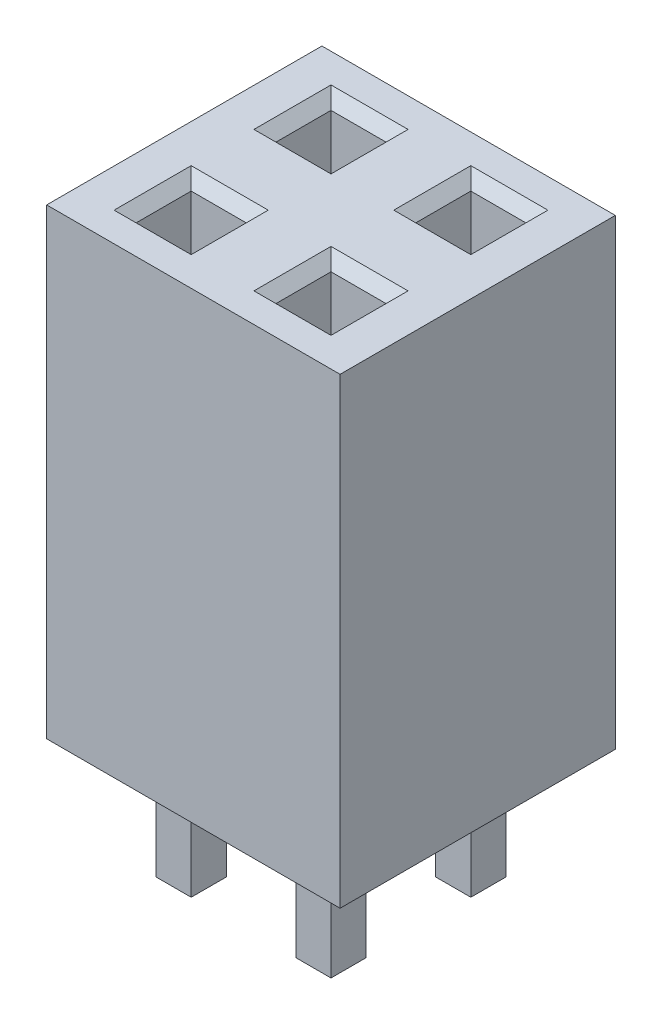
SolidWorks part; units mm, degrees
material "C (Графит)"
ref_plane "Спереди" through (0, 0, 0) normal (0, 0, 1) x (1, 0, 0)
ref_plane "Сверху" through (0, 0, 0) normal (0, 1, 0) x (1, 0, 0)
ref_plane "Справа" through (0, 0, 0) normal (1, 0, 0) x (0, 0, -1)
sketch "Эскиз1" plane through (0, 0, 0) normal (0, 1, 0) x (1, 0, 0)
  line L1 (-1.395, -2.5) -> (1.395, -2.5)
  line L2 (-1.395, -2.5) -> (-1.395, 2.5)
  line L3 (-1.395, 2.5) -> (1.395, 2.5)
  line L4 (1.395, -2.5) -> (1.395, 2.5)
  line L5 (-1.395, -2.5) -> (1.395, 2.5) construction
  line L6 (-1.395, 2.5) -> (1.395, -2.5) construction
  point P0 (0, 0)
  dimension "D1" = 5
  dimension "D2" = 2.79
extrude "Бобышка-Вытянуть1" add sketch "Эскиз1" along normal blind 8.4
sketch "Эскиз2" plane through (0, 8.4, 0) normal (0, 1, 0) x (1, 0, 0)
  line L0 (-1.395, 2.5) -> (-1.395, -2.5) construction
  line L1 (-0.5, 1.77) -> (0.5, 1.77)
  line L2 (-0.5, 1.77) -> (-0.5, 0.77)
  line L3 (-0.5, 0.77) -> (0.5, 0.77)
  line L4 (0.5, 1.77) -> (0.5, 0.77)
  line L5 (-0.5, 1.77) -> (0.5, 0.77) construction
  line L6 (-0.5, 0.77) -> (0.5, 1.77) construction
  line L7 (-1.395, 0) -> (-29.5201, 0) construction
  line L8 (0.5, -1.77) -> (0.5, -0.77)
  line L9 (-0.5, -0.77) -> (0.5, -0.77)
  line L10 (-0.5, -1.77) -> (-0.5, -0.77)
  line L11 (-0.5, -1.77) -> (0.5, -1.77)
  point P0 (0, 1.27)
  dimension "D1" = 1
  dimension "D2" = 1
  dimension "D3" = 1.395
  dimension "D4" = 1.27
extrude "Вырез-Вытянуть1" cut sketch "Эскиз2" against normal blind 8
chamfer "Фаска1" distance 0.2 angle 45 8 edges at (0.5, 8.4, -1.27) (0, 8.4, -0.77) (-0.5, 8.4, -1.27) (0, 8.4, -1.77) (0, 8.4, 1.77) (-0.5, 8.4, 1.27) (0, 8.4, 0.77) (0.5, 8.4, 1.27)
sketch "Эскиз3" plane through (0, 0, 0) normal (0, -1, 0) x (-1, 0, 0)
  line L0 (1.395, 2.5) -> (1.395, -2.5) construction
  line L1 (0.32, 0.95) -> (-0.32, 0.95)
  line L2 (0.32, 0.95) -> (0.32, 1.59)
  line L3 (0.32, 1.59) -> (-0.32, 1.59)
  line L4 (-0.32, 0.95) -> (-0.32, 1.59)
  line L5 (0.32, 0.95) -> (-0.32, 1.59) construction
  line L6 (0.32, 1.59) -> (-0.32, 0.95) construction
  line L7 (1.395, 0) -> (32.9327, 0) construction
  line L8 (0.32, -0.95) -> (-0.32, -0.95)
  line L9 (-0.32, -0.95) -> (-0.32, -1.59)
  line L10 (0.32, -1.59) -> (-0.32, -1.59)
  line L11 (0.32, -0.95) -> (0.32, -1.59)
  point P0 (0, 1.27)
  dimension "D1" = 0.64
  dimension "D2" = 0.64
  dimension "D3" = 1.395
  dimension "D4" = 2.54
extrude "Бобышка-Вытянуть2" add sketch "Эскиз3" along normal blind 2.29
chamfer "Фаска2" distance 0.2 angle 45 8 edges at (0, -2.29, -1.59) (-0.32, -2.29, -1.27) (0, -2.29, -0.95) (0.32, -2.29, -1.27) (0, -2.29, 1.59) (0.32, -2.29, 1.27) (0, -2.29, 0.95) (-0.32, -2.29, 1.27)
pattern_linear "Линейный массив1" count 2 spacing 2.54 along (1, 0, 0) of "Бобышка-Вытянуть1", "Вырез-Вытянуть1", "Фаска1", "Бобышка-Вытянуть2", "Фаска2"
